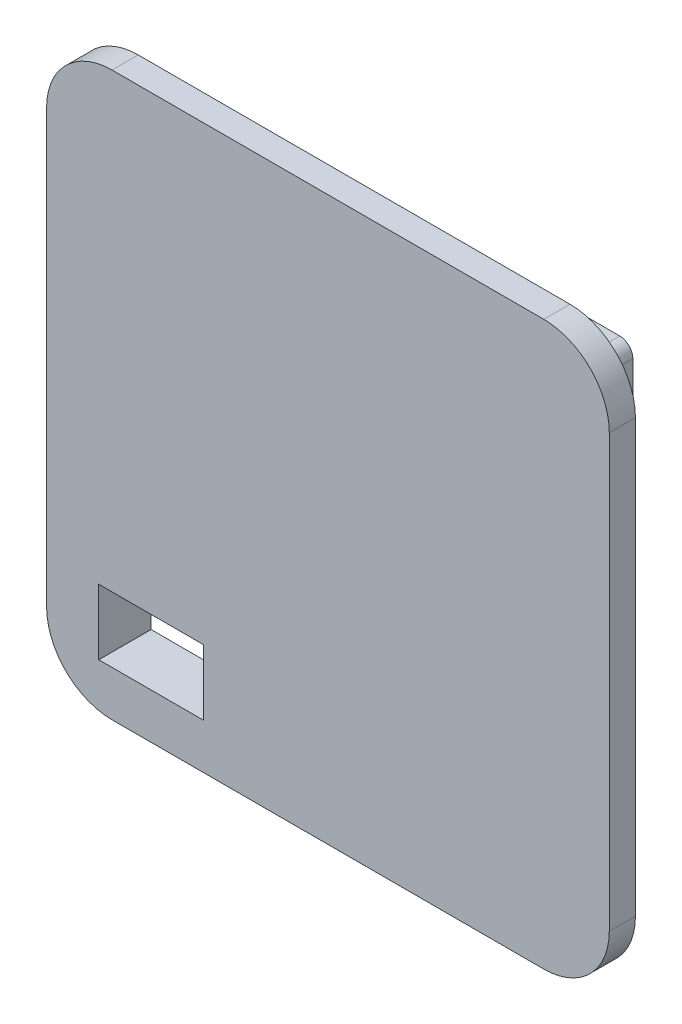
SolidWorks part; units mm, degrees
ref_plane "Front Plane" through (0, 0, 0) normal (1, 0, 0) x (0, 1, 0)
ref_plane "Top Plane" through (0, 0, 0) normal (0, 0, 1) x (0, 1, 0)
ref_plane "Right Plane" through (0, 0, 0) normal (0, 1, 0) x (-1, 0, 0)
sketch "Sketch1" plane through (0, 0, 0) normal (0, 0, 1) x (0, 1, 0)
  line L1 (21.5, -21.5) -> (-21.5, -21.5)
  line L2 (21.5, -21.5) -> (21.5, 21.5)
  line L3 (21.5, 21.5) -> (-21.5, 21.5)
  line L4 (-21.5, -21.5) -> (-21.5, 21.5)
  line L5 (21.5, -21.5) -> (-21.5, 21.5) construction
  line L6 (21.5, 21.5) -> (-21.5, -21.5) construction
  point P0 (0, 0)
  dimension "D1" = 43
  dimension "D2" = 43
extrude "Boss-Extrude1" add sketch "Sketch1" along normal blind 2
fillet "Fillet1" radius 5 4 edges at (21.5, -21.5, 1) (-21.5, -21.5, 1) (-21.5, 21.5, 1) (21.5, 21.5, 1)
sketch "Sketch2" plane through (0, 0, 2) normal (0, 0, 1) x (1, 0, 0)
  line L1 (-9.5127, -18.0346) -> (-17.5127, -18.0346)
  line L2 (-9.5127, -18.0346) -> (-9.5127, -13.0346)
  line L3 (-9.5127, -13.0346) -> (-17.5127, -13.0346)
  line L4 (-17.5127, -18.0346) -> (-17.5127, -13.0346)
  line L5 (-9.5127, -18.0346) -> (-17.5127, -13.0346) construction
  line L6 (-9.5127, -13.0346) -> (-17.5127, -18.0346) construction
  point P0 (-13.5127, -15.5346)
  dimension "D1" = 8
  dimension "D2" = 5
extrude "Cut-Extrude1" cut sketch "Sketch2" against normal through all
sketch "Sketch3" plane through (0, 0, 0) normal (0, 0, -1) x (0, 1, 0)
  line L0 (19.3, -19.3) -> (19.3, 19.3)
  line L1 (19.5, -19.5) -> (-19.5, -19.5)
  line L2 (19.5, -19.5) -> (19.5, 19.5)
  line L3 (19.5, 19.5) -> (-19.5, 19.5)
  line L4 (-19.5, -19.5) -> (-19.5, 19.5)
  line L5 (19.5, -19.5) -> (-19.5, 19.5) construction
  line L6 (19.5, 19.5) -> (-19.5, -19.5) construction
  line L7 (19.3, 19.3) -> (-19.3, 19.3)
  line L8 (-19.3, -19.3) -> (-19.3, 19.3)
  line L9 (19.3, -19.3) -> (-19.3, -19.3)
  point P0 (0, 0)
  line M10 (-13.0346, -9.5127) -> (-13.0346, -17.5127)
  line M11 (-13.0346, -17.5127) -> (-18.0346, -17.5127)
  line M12 (-18.0346, -17.5127) -> (-18.0346, -9.5127)
  line M13 (-18.0346, -9.5127) -> (-13.0346, -9.5127)
  dimension "D1" = 39
  dimension "D2" = 39
  dimension "D3" = 0.2
extrude "Boss-Extrude2" add sketch "Sketch3" along normal blind 2 contours L9 L0 L7 L8 M13 M10 M11 M12
fillet "Fillet3" radius 1 4 edges at (-19.3, 19.3, -1) (19.3, 19.3, -1) (19.3, -19.3, -1) (-19.3, -19.3, -1)
